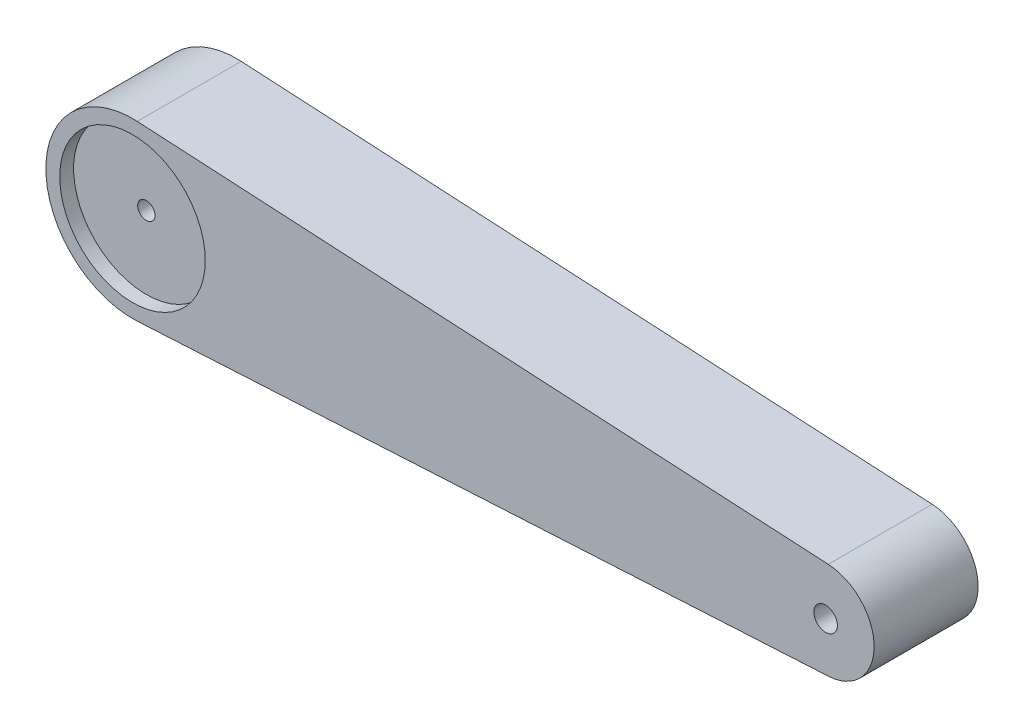
SolidWorks part; units mm, degrees
ref_plane "Front Plane" through (0, 0, 0) normal (0, 0, 1) x (1, 0, 0)
ref_plane "Top Plane" through (0, 0, 0) normal (0, 1, 0) x (1, 0, 0)
ref_plane "Right Plane" through (0, 0, 0) normal (1, 0, 0) x (0, 0, -1)
sketch "Sketch1" plane through (0, 0, 0) normal (0, 0, 1) x (1, 0, 0)
  line L0 (0, 0) -> (100, 0) construction
  line L1 (0.6875, 12.4811) -> (100.385, 6.9894)
  line L2 (0.6875, -12.4811) -> (100.385, -6.9894)
  arc A1 (100.385, -6.9894) -> (100.385, 6.9894) centre (100, 0) ccw
  arc A2 (0.6875, 12.4811) -> (0.6875, -12.4811) centre (0, 0) ccw
  dimension "D1" = 12.5
  dimension "D2" = 14
  dimension "D3" = 100
extrude "Boss-Extrude1" add sketch "Sketch1" along normal blind 15
sketch "Sketch4" plane through (0, 0, 15) normal (0, 0, 1) x (1, 0, 0)
  circle A0 centre (0, 0) radius 10.5
  dimension "D1" = 21
extrude "Cut-Extrude2" cut sketch "Sketch4" against normal blind 2
hole_wizard "M3 Clearance Hole2" positions "Sketch11" profile "Sketch12" hole size "M3" standard "ANSI Metric" end condition through all
sketch "Sketch11" plane through (0, 0, 15) normal (0, 0, 1) x (1, 0, 0)
  point P0 (100, 0)
sketch "Sketch12" plane through (100, 0, 15) normal (1, 0, 0) x (0, -1, 0)
  line L0 (0, 0) -> (0, 15)
  line L1 (0, 15) -> (1.7, 15)
  line L2 (1.7, 15) -> (1.7, 0)
  line L5 (1.7, 0) -> (0, 0)
  line L11 (0, -6.35) -> (0, 107.95) construction
  dimension "Thru Hole Dia." = 3.4
  dimension "Thru Hole Depth" = 15
hole_wizard "M3x0.5 Tapped Hole1" positions "Sketch17" profile "Sketch18" tap size "M3x0.5" standard "ANSI Metric" end condition up to next
sketch "Sketch17" plane through (0, 0, 0) normal (0, 0, -1) x (-1, 0, 0)
  point P0 (0, 0)
sketch "Sketch18" plane through (0, 0, 0) normal (1, 0, 0) x (0, 1, 0)
  line L0 (0, 0) -> (0, 13)
  line L1 (0, 13) -> (1.25, 13)
  line L2 (1.25, 13) -> (1.25, 3.75)
  line L3 (1.25, 3.75) -> (5, 0)
  line L5 (5, 0) -> (0, 0)
  line L6 (-1.25, 3.75) -> (-5, 0) construction
  line L11 (0, -6.35) -> (0, 107.95) construction
  dimension "Thru Tap Drill Dia." = 2.5
  dimension "Thru Tap Drill Depth" = 13
  dimension "Near C'Sink Dia." = 10
  dimension "Near C'Sink Angle" = 90
